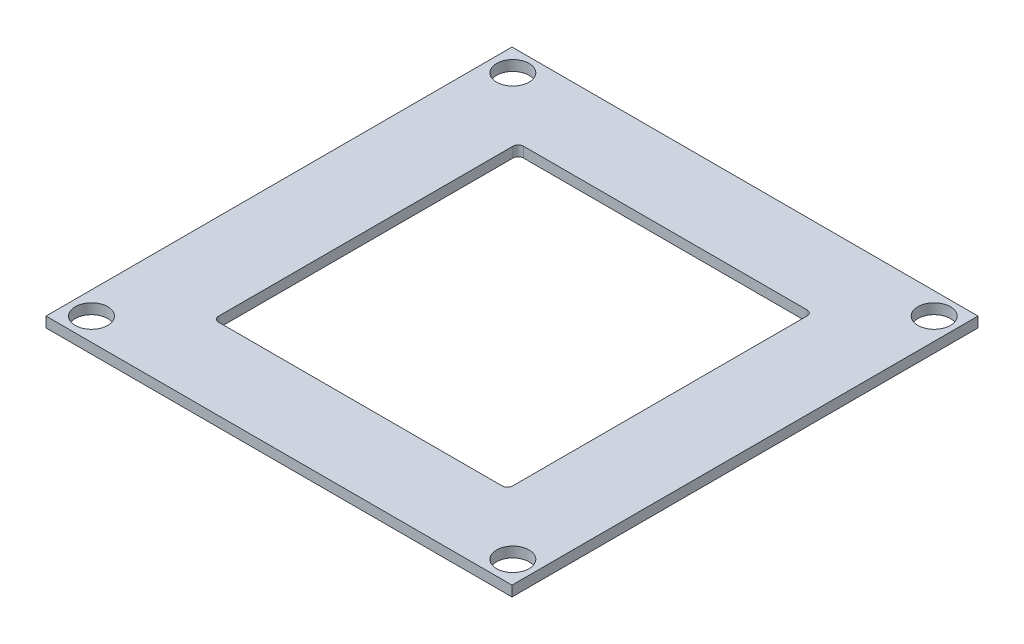
SolidWorks part; units mm, degrees
material "Acrylic (Medium-high impact)"
ref_plane "Front" through (0, 0, 0) normal (0, 0, 1) x (1, 0, 0)
ref_plane "Top" through (0, 0, 0) normal (0, 1, 0) x (1, 0, 0)
ref_plane "Right" through (0, 0, 0) normal (1, 0, 0) x (0, 0, -1)
sketch "Sketch1" plane through (0, 0, 0) normal (0, 1, 0) x (1, 0, 0)
  line L1 (0, -143.396) -> (286.792, -143.396)
  line L2 (0, -143.396) -> (0, 143.396)
  line L3 (0, 143.396) -> (286.792, 143.396)
  line L4 (286.792, -143.396) -> (286.792, 143.396)
  point P6 (0, 0)
  dimension "D1" = 286.792
  dimension "D2" = 286.792
extrude "Boss-Extrude1" add sketch "Sketch1" along normal blind 6.35
other "PropertyManager"
sketch "Sketch2" plane through (0, 0, 0) normal (0, -1, 0) x (1, 0, 0)
  line L0 (230.9625, -90.9002) -> (56.3375, 90.3922) construction
  line L2 (234.14, 93.5697) -> (53.16, 93.5697)
  line L3 (234.14, 93.5697) -> (234.14, -94.0777)
  line L4 (234.14, -94.0777) -> (53.16, -94.0777)
  line L5 (53.16, 93.5697) -> (53.16, -94.0777)
  line L6 (234.14, 93.5697) -> (53.16, -94.0777) construction
  line L7 (234.14, -94.0777) -> (53.16, 93.5697) construction
  circle A0 centre (273.3, -129.904) radius 10
  circle A1 centre (14, -129.904) radius 10
  circle A2 centre (14, 129.396) radius 10
  circle A3 centre (273.3, 129.396) radius 10
  arc A4 (53.1625, -92.9527) -> (54.285, -94.0753) centre (53.7213, -93.5165) ccw construction
  point P16 (143.65, -0.254)
extrude "Cut-Extrude1" cut sketch "Sketch2" against normal blind 6.35
fillet "Fillet1" radius 3.175 4 edges at (53.16, 3.175, -94.0777) (234.14, 3.175, -94.0777) (234.14, 3.175, 93.5697) (53.16, 3.175, 93.5697)
equation "\"thick\"= .25in"
equation "\"tol\"= .01"
equation "\"ftprnt\"= 30cm"
equation "\"D1@Sketch1\"      = \"ftprnt\"-(\"thick\"*2)-(\"tol\"*2)"
equation "\"D1@Boss-Extrude1\"=\"thick\""
equation "\"height\"= 5cm"
equation "\"D2@Sketch1\"        = \"ftprnt\"-(\"thick\"*2)-(\"tol\"*2)"
